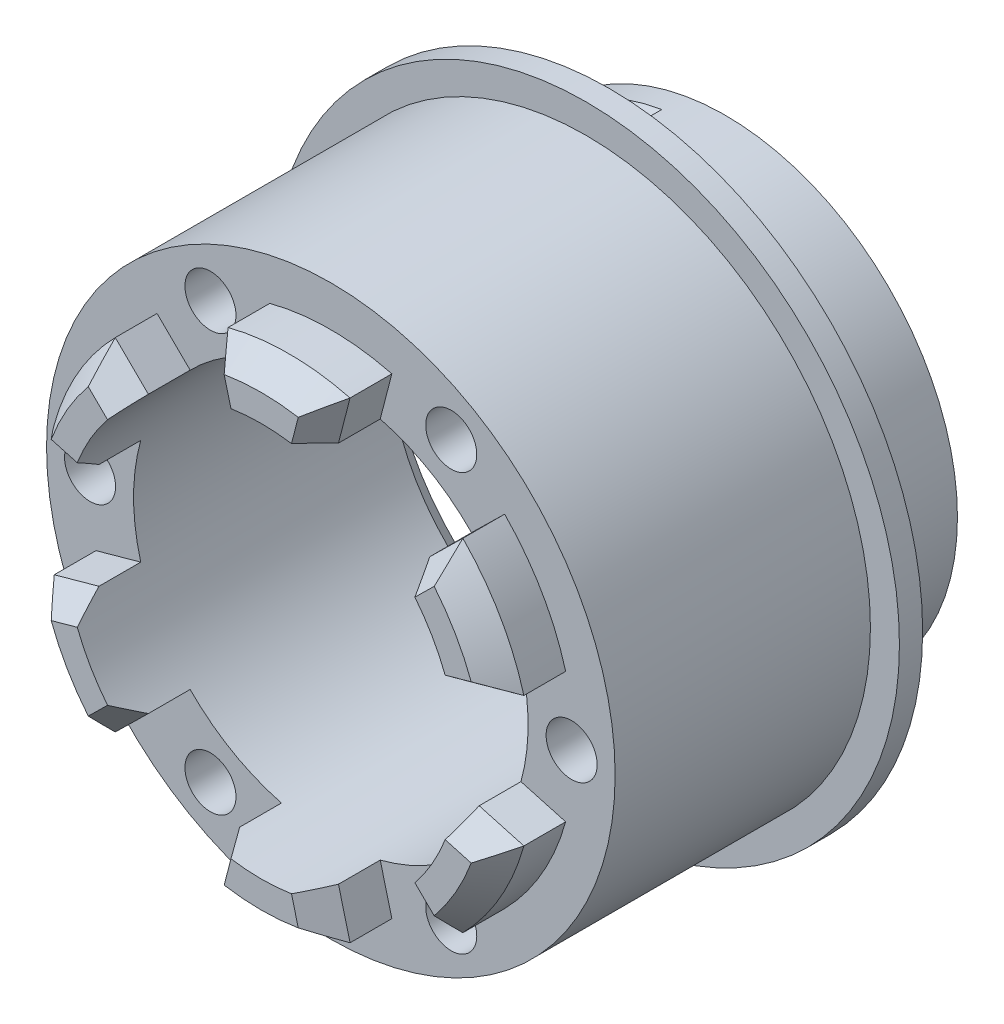
SolidWorks part; units mm, degrees
ref_plane "정면" through (0, 0, 0) normal (0, 0, 1) x (1, 0, 0)
ref_plane "윗면" through (0, 0, 0) normal (0, 1, 0) x (1, 0, 0)
ref_plane "우측면" through (0, 0, 0) normal (1, 0, 0) x (0, 0, -1)
sketch "스케치1" plane through (0, 0, 0) normal (0, 0, 1) x (1, 0, 0)
  circle A0 centre (0, 0) radius 10
  dimension "D1" = 20
extrude "보스-돌출1" add sketch "스케치1" along normal blind 2
sketch "스케치2" plane through (0, 0, 2) normal (0, 0, 1) x (1, 0, 0)
  circle A0 centre (0, 0) radius 10
  circle A1 centre (0, 0) radius 8.5
  circle A5 centre (0, 0) radius 10 construction
  dimension "D1" = 1.5
extrude "보스-돌출2" add sketch "스케치2" along normal blind 3
sketch "스케치4" plane through (0, 0, 5) normal (0, 0, 1) x (1, 0, 0)
  circle A0 centre (0, 0) radius 13.5
  circle A1 centre (0, 0) radius 8.5
  circle A2 centre (0, 0) radius 8.5 construction
  dimension "D1" = 27
extrude "보스-돌출3" add sketch "스케치4" along normal blind 1
sketch "스케치5" plane through (0, 0, 6) normal (0, 0, 1) x (1, 0, 0)
  circle A0 centre (0, 0) radius 8.5
  circle A1 centre (0, 0) radius 12.25
  circle A2 centre (0, 0) radius 8.5 construction
  dimension "D1" = 24.5
extrude "보스-돌출4" add sketch "스케치5" along normal blind 11
sketch "스케치6" plane through (0, 0, 17) normal (0, 0, 1) x (1, 0, 0)
  circle A0 centre (0, 0) radius 10.375 construction
  circle A6 centre (0, 0) radius 8.5 construction
  circle A8 centre (10.375, 0) radius 1.1
  circle A9 centre (5.1875, -8.985) radius 1.1
  circle A10 centre (-5.1875, -8.985) radius 1.1
  circle A11 centre (-10.375, 0) radius 1.1
  circle A12 centre (-5.1875, 8.985) radius 1.1
  circle A13 centre (5.1875, 8.985) radius 1.1
  point P19 (0, 0)
  point P20 (0, 0)
  dimension "D1" = 1.875
  dimension "D2" = 2.2
  dimension "D3" = 6
extrude "컷-돌출1" cut sketch "스케치6" against normal blind 8
sketch "스케치7" plane through (0, 0, 0) normal (0, 0, -1) x (-1, 0, 0)
  circle A0 centre (0, 0) radius 7 construction
  circle A5 centre (0, 0) radius 3
  circle A6 centre (-7, 0) radius 1.15
  circle A7 centre (7, 0) radius 1.15
  circle A9 centre (0, 7) radius 1.15
  circle A11 centre (0, -7) radius 1.15
  dimension "D1" = 14
  dimension "D2" = 2.3
  dimension "D4" = 6
extrude "컷-돌출2" cut sketch "스케치7" against normal through all
sketch "스케치10" plane through (0, 0, 17) normal (0, 0, 1) x (1, 0, 0)
  line L0 (-2.1282, 8.2293) -> (-2.629, 10.1656)
  line L2 (6.0626, 5.9577) -> (7.4891, 7.3595)
  line L4 (-8.1909, 2.2715) -> (-10.1181, 2.806)
  line L6 (8.1909, -2.2715) -> (10.1181, -2.806)
  line L8 (2.1282, -8.2293) -> (2.629, -10.1656)
  line L10 (-6.0626, -5.9577) -> (-7.4891, -7.3595)
  line L12 (-6.0626, 5.9577) -> (-7.4891, 7.3595)
  line L14 (2.1282, 8.2293) -> (2.629, 10.1656)
  line L16 (8.1909, 2.2715) -> (10.1181, 2.806)
  line L18 (6.0626, -5.9577) -> (7.4891, -7.3595)
  line L20 (-2.1282, -8.2293) -> (-2.629, -10.1656)
  line L22 (-8.1909, -2.2715) -> (-10.1181, -2.806)
  arc A0 (-7.4891, 7.3595) -> (-10.1181, 2.806) centre (0, 0) ccw
  arc A1 (-8.1909, -2.2715) -> (-6.0626, -5.9577) centre (0, 0) ccw
  arc A2 (2.629, 10.1656) -> (-2.629, 10.1656) centre (0, 0) ccw
  arc A3 (10.1181, 2.806) -> (7.4891, 7.3595) centre (0, 0) ccw
  arc A4 (7.4891, -7.3595) -> (10.1181, -2.806) centre (0, 0) ccw
  arc A5 (-2.629, -10.1656) -> (2.629, -10.1656) centre (0, 0) ccw
  arc A6 (-10.1181, -2.806) -> (-7.4891, -7.3595) centre (0, 0) ccw
  arc A7 (-2.1282, -8.2293) -> (2.1282, -8.2293) centre (0, 0) ccw
  arc A8 (6.0626, -5.9577) -> (8.1909, -2.2715) centre (0, 0) ccw
  arc A9 (8.1909, 2.2715) -> (6.0626, 5.9577) centre (0, 0) ccw
  arc A10 (2.1282, 8.2293) -> (-2.1282, 8.2293) centre (0, 0) ccw
  arc A11 (-6.0626, 5.9577) -> (-8.1909, 2.2715) centre (0, 0) ccw
  circle A12 centre (0, 0) radius 8.5 construction
  circle A13 centre (0, 0) radius 8.5 construction
  point P30 (0, 0)
  point P48 (0, 0)
  point P61 (0, 0)
  dimension "D1" = 2
extrude "보스-돌출5" add sketch "스케치10" along normal blind 3
chamfer "모따기1" distance 1.2 angle 35 18 edges at (-9.1545, -2.5388, 20) (-6.7759, -6.6586, 20) (-2.3786, -9.1974, 20) (2.3786, -9.1974, 20) (9.1545, -2.5388, 20) (6.7759, -6.6586, 20) (6.7759, 6.6586, 20) (9.1545, 2.5388, 20) (2.3786, 9.1974, 20) (-2.3786, 9.1974, 20) (-6.7759, 6.6586, 20) (-9.1545, 2.5388, 20) (-9.0933, -5.25, 20) (0, -10.5, 20) (9.0933, -5.25, 20) (9.0933, 5.25, 20) (0, 10.5, 20) (-9.0933, 5.25, 20)
sketch "스케치11" plane through (0, 0, 0) normal (0, 0, -1) x (-1, 0, 0)
  line L0 (0, 0) -> (1.7365, 9.8481)
  line L1 (0, 0) -> (1.7365, -9.8481)
  line L2 (0, 0) -> (10, 0) construction
  circle A0 centre (0, 0) radius 10
  circle M6 centre (7, 0) radius 1.15
  circle M9 centre (0, 0) radius 3
  circle M10 centre (0, 0) radius 10
  dimension "D1" = 80
  dimension "D2" = 80
extrude "컷-돌출3" cut sketch "스케치11" against normal blind 3 from offset 2 contours L2 A0 L0 M9 M6 | L2 L1 M9 M10 M6 offset against normal yes
chamfer "모따기2" distance 1 angle 45 2 edges at (-8.5, 0, 5) (-10, 0, 2)
